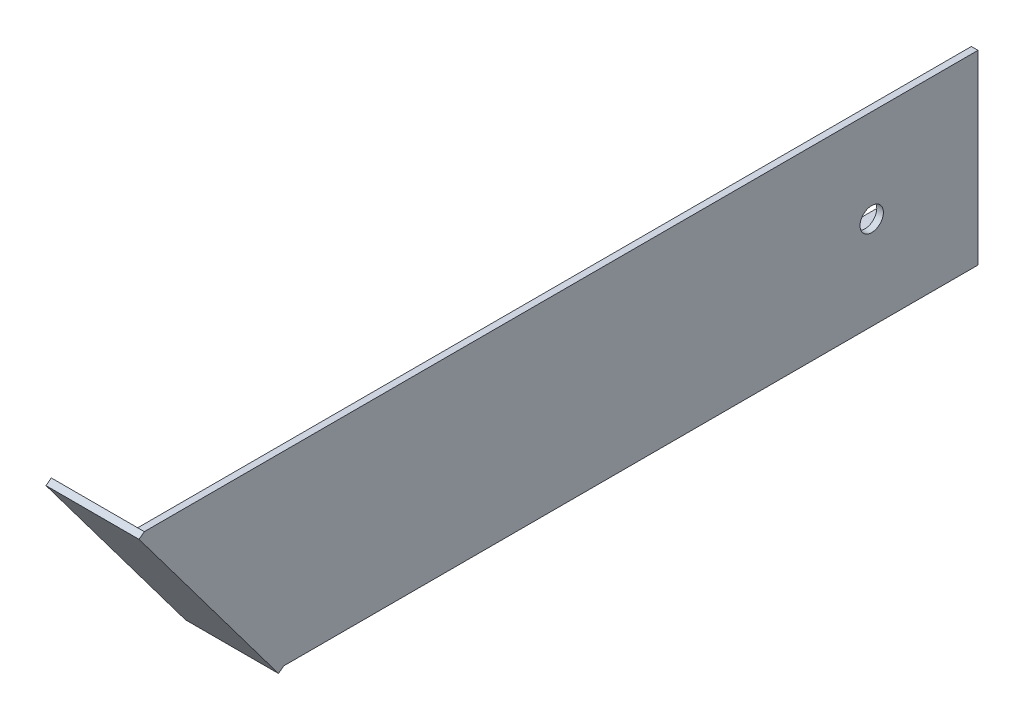
SolidWorks part; units mm, degrees
material "Galvanized Steel"
ref_plane "Front" through (0, 0, 0) normal (0, 0, 1) x (1, 0, 0)
ref_plane "Top" through (0, 0, 0) normal (0, 1, 0) x (1, 0, 0)
ref_plane "Right" through (0, 0, 0) normal (1, 0, 0) x (0, 0, -1)
sketch "Sketch1" plane through (0, 0, 0) normal (0, 0, 1) x (1, 0, 0)
  line L0 (3.175, 88.9) -> (3.175, 3.175)
  line L1 (0, 0) -> (44.45, 0)
  line L2 (0, 0) -> (0, 88.9)
  line L3 (0, 88.9) -> (3.175, 88.9)
  line L4 (44.45, 0) -> (44.45, 3.175)
  line L5 (3.175, 3.175) -> (44.45, 3.175)
  dimension "D1" = 44.45
  dimension "D2" = 3.175
  dimension "D3" = 88.9
extrude "Boss-Extrude1" add sketch "Sketch1" along normal mid plane 398.4625
sketch "Sketch4" plane through (3.175, 0, 0) normal (1, 0, 0) x (0, 0, -1)
  line L0 (199.2312, 3.175) -> (199.2312, 88.9) construction
  line L1 (199.2312, 88.9) -> (199.2312, 0) construction
  line L2 (-199.2312, 88.9) -> (-132.556, 0)
  line L3 (-199.2312, 0) -> (199.2312, 0) construction
  line L4 (-132.556, 0) -> (-199.2312, 0)
  line L5 (-199.2312, 0) -> (-199.2312, 88.9)
  circle A0 centre (148.4313, 44.45) radius 5.588
  point P6 (199.2312, 44.45)
  dimension "D2" = 11.176
  dimension "D1" = 50.8
  dimension "D3" = 53.13
extrude "Cut-Extrude3" cut sketch "Sketch4" along normal through all both and the other way through all
sketch "Sketch5" plane through (0, -63.6269, 84.8356) normal (0, -0.6, 0.8) x (1, 0, 0)
  line L1 (0, 79.5338) -> (44.45, 79.5338)
  line L2 (0, 79.5338) -> (0, 190.6589)
  line L3 (0, 190.6589) -> (44.45, 190.6589)
  line L4 (44.45, 79.5338) -> (44.45, 190.6589)
extrude "Boss-Extrude3" add sketch "Sketch5" along normal blind 3.175
mirror "Mirror1" about plane through (0, 0, 0) normal (1, 0, 0) of bodies 105
delete or keep bodies "Body-Delete/Keep 1" type delete bodies bodies 105
